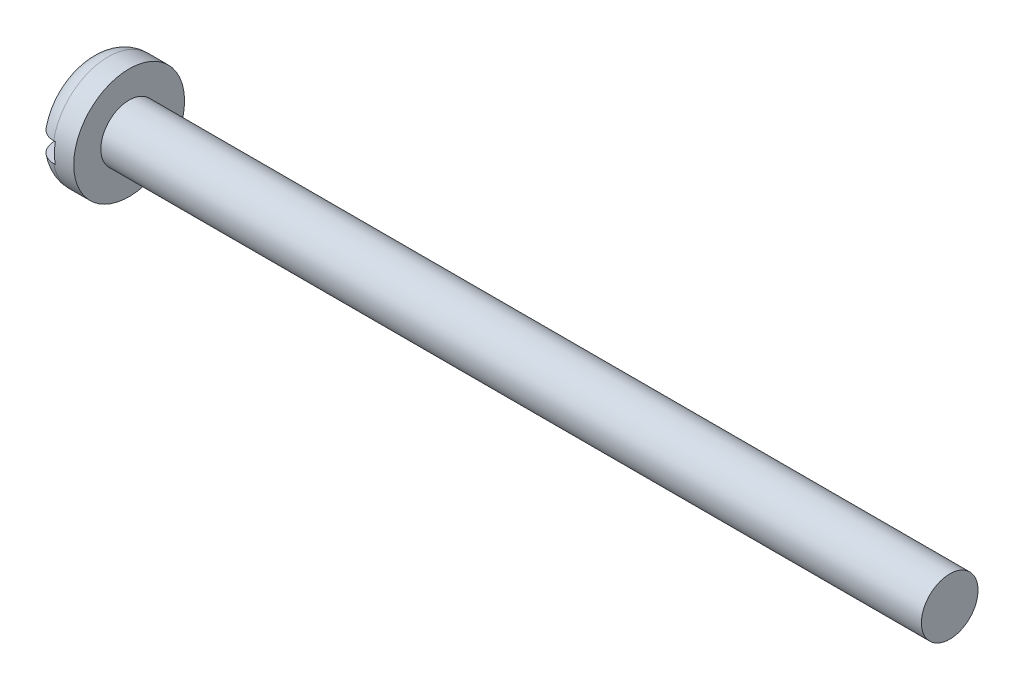
SolidWorks part; units mm, degrees
ref_plane "Plane1" through (0, 0, 0) normal (0, 0, 1) x (1, 0, 0)
ref_plane "Plane2" through (0, 0, 0) normal (0, 1, 0) x (1, 0, 0)
ref_plane "Plane3" through (0, 0, 0) normal (1, 0, 0) x (0, 0, -1)
sketch "BodySke" plane through (0, 0, 0) normal (0, 0, 1) x (1, 0, 0)
  line L0 (2.4638, 1.7526) -> (2.4638, 3.429)
  line L1 (0, 0) -> (0, 2.2606)
  line L2 (-25.4, 0) -> (127, 0) construction
  line L3 (53.2638, 0) -> (0, 0)
  line L4 (2.4638, 1.7526) -> (53.2638, 1.7526)
  line L5 (53.2638, 1.7526) -> (53.2638, 0)
  line L6 (1.1684, 3.429) -> (2.4638, 3.429)
  line L7 (2.4638, -1.7526) -> (53.2638, -1.7526) construction
  line L8 (0, -3.429) -> (2.4638, -3.429) construction
  line L9 (3.2563, 3.3401) -> (3.2563, -6.1849) construction
  line L10 (2.4638, 6.35) -> (2.4638, -3.175) construction
  arc A0 (0, 2.2606) -> (1.1684, 3.429) centre (1.1684, 2.2606) cw
  point P15 (0, 3.429)
  dimension "Head_fillet_rad" = 1.1684
  dimension "Diameter" = 3.5052
  dimension "Length" = 50.8
  dimension "Head_ht" = 2.4638
  dimension "Head_dia" = 6.858
  dimension "Advance" = 0.7925
  dimension "Thread_nom" = 50.8
revolve "Base-Revolve" add sketch "BodySke" angle 360 about L2
cosmetic thread "ThreadCosmetic" parameters "Thread_length"=50.0075, "Thread_minor"=2.5603
sketch "Sketch2" plane through (0, 0, 0) normal (1, 0, 0) x (0, 0, -1)
  line L0 (3.429, -0.6096) -> (-3.429, -0.6096)
  line L1 (3.429, -0.6096) -> (3.429, 0.6096)
  line L2 (-3.429, 0.6096) -> (3.429, 0.6096)
  line L3 (-3.429, 0.6096) -> (-3.429, -0.6096)
  dimension "D1" = 6.858
  dimension "Slot_width" = 1.2192
  dimension "D2" = 3.429
  dimension "D3" = 0.6096
extrude "Slot" cut sketch "Sketch2" along normal blind 1.27
sketch "ThdSchSke" plane through (0, 0, 0) normal (0, 0, 1) x (1, 0, 0)
  line L0 (3.2563, -1.2802) -> (2.9255, -1.7526)
  line L1 (3.2563, -1.2802) -> (3.5871, -1.7526)
  line L2 (3.5871, -1.7526) -> (3.5871, -2.1908)
  line L3 (-3.175, 0) -> (5.1513, 0) construction
  line L5 (3.5871, -2.1908) -> (2.9255, -2.1908)
  line L6 (2.9255, -2.1908) -> (2.9255, -1.7526)
  dimension "Diameter" = 3.5052
  dimension "SideAngle" = 55
  dimension "VeeAngle" = 70
  dimension "Thread_minor" = 2.5603
  dimension "Overcut" = 4.3815
  dimension "Start" = 3.2563
revolve "ThreadSchematic" [suppressed] cut sketch "ThdSchSke" angle 360 about L3
pattern_linear "ThdSchPat" [suppressed]
equation "\"D1@Sketch2\" = \"Head_dia@BodySke\""
equation "\"D2@Sketch2\" = \"D1@Sketch2\" / 2"
equation "\"D3@Sketch2\" = \"Slot_width@Sketch2\" / 2"
equation "\"Thread_length@ThreadCosmetic\" = ((sgn( (\"Length@BodySke\" - \"Advance@BodySke\" ) - \"Thread_nom@BodySke\" )-1)*( (\"Length@BodySke\" - \"Advance@BodySke\" ) - \"Thread_nom@BodySke\" ))/-2+ \"Thread_nom@BodySke\""
equation "\"Thread_minor@ThdSchSke\" = \"Thread_minor@ThreadCosmetic\""
equation "\"Diameter@ThdSchSke\" = \"Diameter@BodySke\""
equation "\"Overcut@ThdSchSke\" = \"Diameter@BodySke\" * 1.25"
equation "\"Start@ThdSchSke\" = \"Head_ht@BodySke\" + \"Length@BodySke\" - \"Thread_length@ThreadCosmetic\"  '---Non-countersunk---"
equation "\"Num_threads@ThdSchPat\" = int( \"Thread_length@ThreadCosmetic\" / \"Advance@BodySke\" + 0.999 )  + 1"
equation "\"Advance@ThdSchPat\" = \"Thread_length@ThreadCosmetic\" /  (\"Num_threads@ThdSchPat\" - 1) 'relax it"
